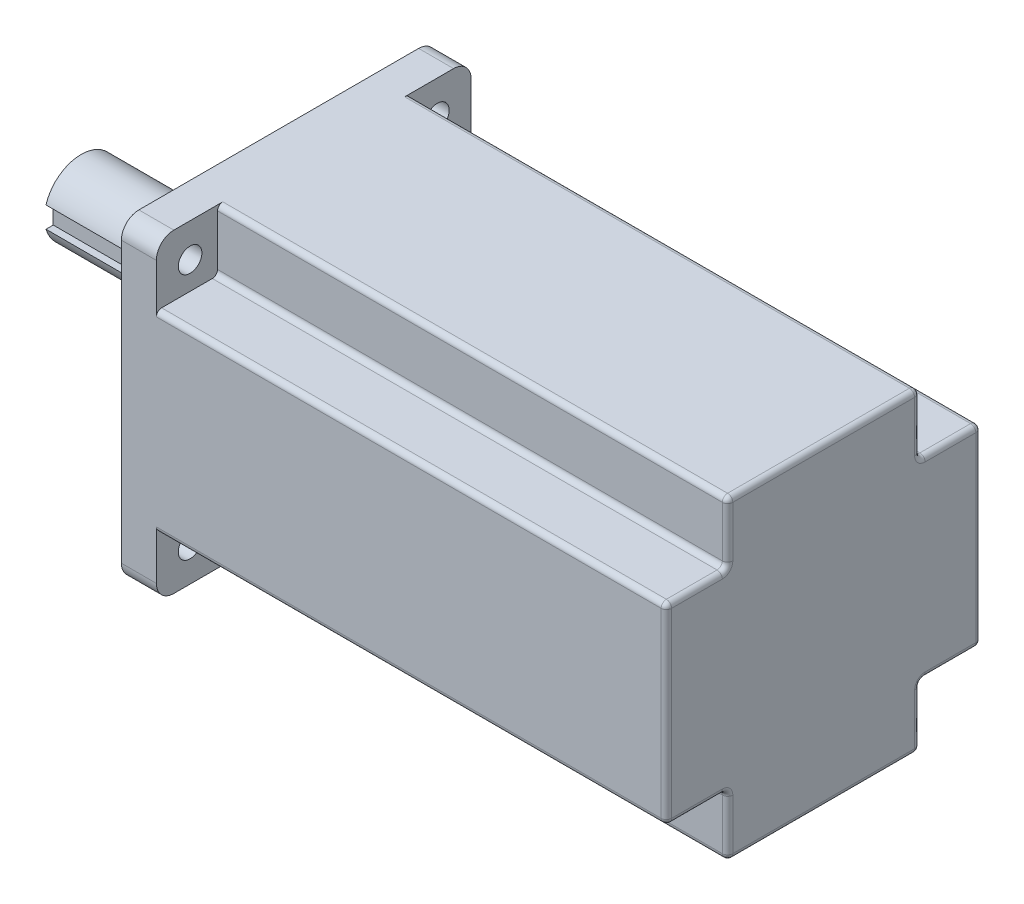
SolidWorks part; units mm, degrees
ref_plane "Front Plane" through (0, 0, 0) normal (0, 0, 1) x (1, 0, 0)
ref_plane "Top Plane" through (0, 0, 0) normal (0, 1, 0) x (1, 0, 0)
ref_plane "Right Plane" through (0, 0, 0) normal (1, 0, 0) x (0, 0, -1)
sketch "Sketch1" plane through (0, 0, 0) normal (1, 0, 0) x (0, 0, -1)
  line L1 (-90, -90) -> (90, -90)
  line L2 (-90, -90) -> (-90, 90)
  line L3 (-90, 90) -> (90, 90)
  line L4 (90, -90) -> (90, 90)
  line L5 (-90, -90) -> (90, 90) construction
  line L6 (-90, 90) -> (90, -90) construction
  point P0 (0, 0)
  dimension "D1" = 180
extrude "Boss-Extrude1" add sketch "Sketch1" along normal blind 20
fillet "Fillet1" radius 10 4 edges at (10, -90, 90) (10, -90, -90) (10, 90, -90) (10, 90, 90)
sketch "Sketch2" plane through (20, 0, 0) normal (1, 0, 0) x (0, 0, -1)
  line L0 (80, 90) -> (-80, 90) construction
  line L1 (-55, 90) -> (55, 90)
  line L2 (-55, 90) -> (-55, 55)
  line L3 (-55, -90) -> (55, -90)
  line L4 (55, 90) -> (55, 55)
  line L5 (-80, -90) -> (80, -90) construction
  line L6 (90, -80) -> (90, 80) construction
  line L7 (90, 55) -> (55, 55)
  line L8 (90, 55) -> (90, -55)
  line L9 (90, -55) -> (55, -55)
  line L10 (-90, 55) -> (-90, -55)
  line L11 (-90, 80) -> (-90, -80) construction
  line L12 (90, 0) -> (0, 0) construction
  line L13 (0, 0) -> (0, 90) construction
  line L14 (55, -55) -> (55, -90)
  line L15 (-55, 55) -> (-90, 55)
  line L16 (-55, -55) -> (-55, -90)
  line L17 (-55, -55) -> (-90, -55)
  dimension "D1" = 35
extrude "Boss-Extrude2" add sketch "Sketch2" along normal blind 291.7
sketch "Sketch3" plane through (0, 0, 0) normal (-1, 0, 0) x (0, 0, 1)
  circle A0 centre (0, 0) radius 57.15
  dimension "D1" = 114.3
extrude "Boss-Extrude3" add sketch "Sketch3" along normal blind 4
sketch "Sketch4" plane through (0, 0, 0) normal (-1, 0, 0) x (0, 0, 1)
  circle A0 centre (0, 0) radius 21
  dimension "D1" = 42
extrude "Boss-Extrude4" add sketch "Sketch4" along normal blind 113
sketch "Sketch6" plane through (0, 0, 0) normal (0, 0, 1) x (1, 0, 0)
  line L0 (-113, 0) -> (-29, 0) construction
  line L1 (-113, 21) -> (-113, -21) construction
  line L2 (-113, 6) -> (-29, 6)
  line L3 (-113, -6) -> (-29, -6)
  arc A0 (-113, 6) -> (-113, -6) centre (-113, 0) ccw
  arc A1 (-29, -6) -> (-29, 6) centre (-29, 0) ccw
  point P5 (-71, 0)
  dimension "D1" = 12
  dimension "D2" = 84
extrude "Cut-Extrude1" cut sketch "Sketch6" along normal blind 113 from offset 16
hole_wizard "M16x2.0 Tapped Hole1" positions "Sketch7" profile "Sketch8" tap size "M16x2.0" standard "ANSI Metric"
sketch "Sketch7" plane through (-113, 0, 0) normal (-1, 0, 0) x (0, 0, 1)
  point P0 (0, 0)
sketch "Sketch8" plane through (-113, 0, 0) normal (0, 1, 0) x (0, 0, 1)
  line L0 (0, 0) -> (0, 36.206)
  line L1 (0, 36.206) -> (7, 32)
  line L2 (7, 32) -> (7, 1.025)
  line L3 (7, 1.025) -> (8.025, 0)
  line L5 (8.025, 0) -> (0, 0)
  line L6 (-7, 1.025) -> (-8.025, 0) construction
  line L10 (0, 36.206) -> (-7, 32) construction
  line L11 (0, -6.35) -> (0, 107.95) construction
  dimension "Tap Drill Dia." = 14
  dimension "Tap Drill Depth" = 32
  dimension "Near C'Sink Dia." = 16.05
  dimension "Near C'Sink Angle" = 90
  dimension "Drill Angle" = 118
cosmetic thread "Hole Thread1" parameters "D1"=32, "D2"=16
sketch "Sketch9" plane through (0, 0, 0) normal (-1, 0, 0) x (0, 0, 1)
  line L1 (-70.7107, -70.7107) -> (70.7107, -70.7107) construction
  line L2 (-70.7107, -70.7107) -> (-70.7107, 70.7107) construction
  line L3 (-70.7107, 70.7107) -> (70.7107, 70.7107) construction
  line L4 (70.7107, -70.7107) -> (70.7107, 70.7107) construction
  line L5 (-70.7107, -70.7107) -> (70.7107, 70.7107) construction
  line L6 (-70.7107, 70.7107) -> (70.7107, -70.7107) construction
  circle A0 centre (70.7107, 70.7107) radius 6.75
  circle A1 centre (70.7107, -70.7107) radius 6.75
  circle A2 centre (-70.7107, -70.7107) radius 6.75
  circle A3 centre (-70.7107, 70.7107) radius 6.75
  point P0 (0, 0)
  dimension "D2" = 13.5
  dimension "D1" = 200
extrude "Cut-Extrude2" cut sketch "Sketch9" against normal blind 20
fillet "Fillet2" radius 3 24 edges at (165.85, 90, 55) (165.85, 55, 55) (165.85, 55, 90) (165.85, -55, 90) (165.85, -55, 55) (165.85, -90, 55) (165.85, -90, -55) (165.85, -55, -55) (165.85, -55, -90) (165.85, 55, -90) (165.85, 55, -55) (165.85, 90, -55) (311.7, 90, 0) (311.7, 72.5, -55) (311.7, 55, -72.5) (311.7, 0, -90) (311.7, -55, -72.5) (311.7, -72.5, -55) (311.7, -90, 0) (311.7, -72.5, 55) (311.7, -55, 72.5) (311.7, 0, 90) (311.7, 55, 72.5) (311.7, 72.5, 55)
